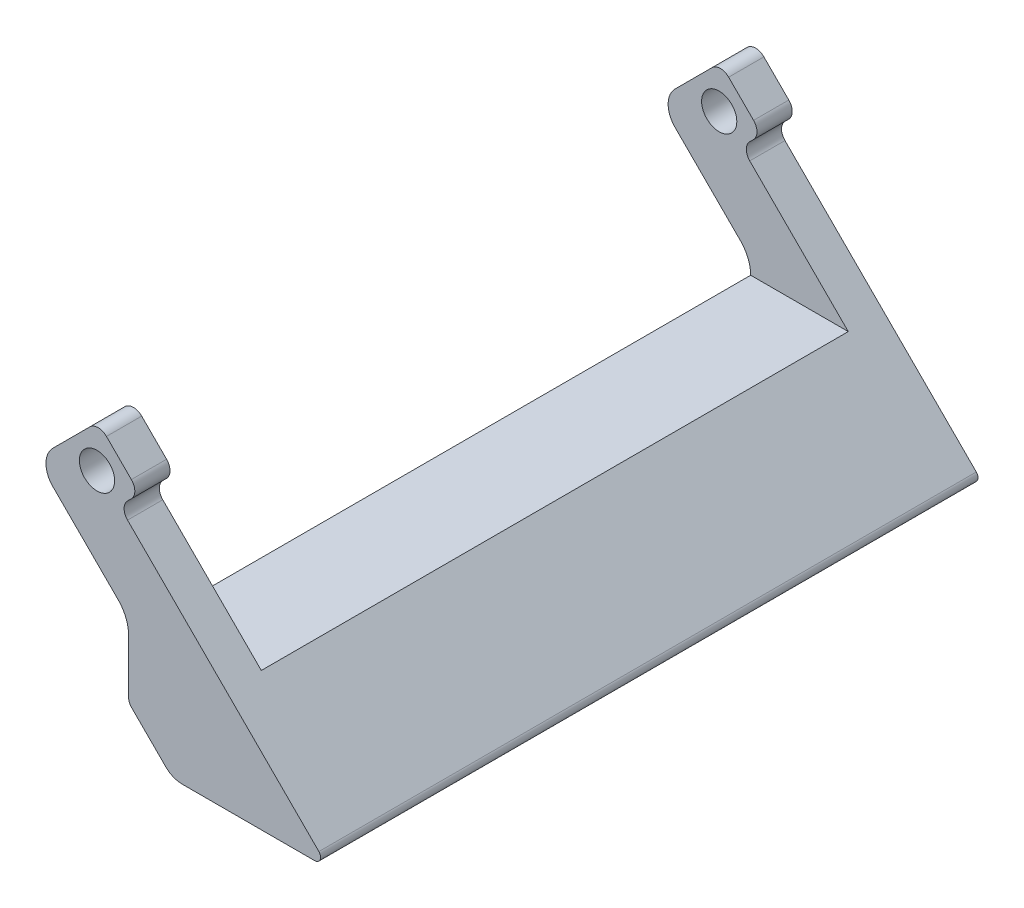
SolidWorks part; units mm, degrees
material "1060-H12"
ref_plane "Front Plane" through (0, 0, 0) normal (0, 0, 1) x (1, 0, 0)
ref_plane "Top Plane" through (0, 0, 0) normal (0, 1, 0) x (1, 0, 0)
ref_plane "Right Plane" through (0, 0, 0) normal (1, 0, 0) x (0, 0, -1)
sketch "Sketch1" plane through (0, 0, 0) normal (0, 0, 1) x (1, 0, 0)
  line L0 (30.0967, -21) -> (76.9648, -21)
  line L1 (3.6822, -19.5) -> (18.5462, -19.5)
  line L2 (-9.1152, 9.3685) -> (-1.6411, 1.8944)
  line L3 (2.6015, -0.934) -> (2.9274, -0.6081)
  line L4 (2.9274, 0.8061) -> (0.8061, 2.9274)
  line L5 (-0.6081, 2.9274) -> (-1.6411, 1.8944)
  line L6 (-1.6411, 1.8944) -> (-3.7625, -0.2269)
  line L7 (-3.7625, -3.0553) -> (1.8035, -8.6213)
  line L8 (2.6822, -10.7426) -> (2.6822, -18.5)
  line L9 (2.6015, -2.3482) -> (18.8997, -18.6464)
  circle A0 centre (0, 0) radius 1.5
  circle A1 centre (30.0967, 0.35) radius 21.35
  arc A2 (2.9274, -0.6081) -> (2.9274, 0.8061) centre (2.2203, 0.099) ccw
  arc A3 (0.8061, 2.9274) -> (-0.6081, 2.9274) centre (0.099, 2.2203) ccw
  arc A4 (2.6822, -18.5) -> (3.6822, -19.5) centre (3.6822, -18.5) ccw
  arc A5 (2.6015, -0.934) -> (2.6015, -2.3482) centre (3.3086, -1.6411) ccw
  arc A6 (-3.7625, -0.2269) -> (-3.7625, -3.0553) centre (-2.3482, -1.6411) ccw
  arc A7 (18.5462, -19.5) -> (18.8997, -18.6464) centre (18.5462, -19) ccw
  arc A8 (1.8035, -8.6213) -> (2.6822, -10.7426) centre (-0.3178, -10.7426) cw
  point P10 (15, -14.7467)
  point P23 (2.6822, -19.5)
  point P26 (1.8944, -1.6411)
  point P33 (2.6822, -9.5)
  dimension "D1" = 3
  dimension "D4" = 42.7
  dimension "D12" = 1
  dimension "D13" = 1
  dimension "D14" = 2
  dimension "D15" = 0.5
  dimension "D16" = 3
  dimension "D2" = 21
  dimension "D3" = 1.5
  dimension "D5" = 45
  dimension "D6" = 15
  dimension "D7" = 2.5
  dimension "D8" = 2.5
  dimension "D9" = 10
  dimension "D10" = 5
  dimension "D11" = 2.64
extrude "Boss-Extrude1" add sketch "Sketch1" along normal blind 3 contours L7 A8 L8 A4 L1 A7 L9 A5 L3 A2 L4 A3 L5 L6 A6 A0
sketch "Sketch2" plane through (0, 0, 3) normal (0, 0, 1) x (1, 0, 0)
  line L0 (2.6015, -2.3482) -> (18.8997, -18.6464) construction
  line L1 (3.6822, -19.5) -> (18.5462, -19.5) construction
  line L2 (2.6822, -10.7426) -> (2.6822, -18.5) construction
  line L3 (2.6015, -2.3482) -> (18.8997, -18.6464)
  line L4 (3.6822, -19.5) -> (18.5462, -19.5)
  line L5 (2.6822, -10.7426) -> (2.6822, -18.5)
  line L6 (2.6822, -10.7426) -> (10.9959, -10.7426)
  arc A0 (18.5462, -19.5) -> (18.8997, -18.6464) centre (18.5462, -19) ccw construction
  arc A1 (2.6822, -18.5) -> (3.6822, -19.5) centre (3.6822, -18.5) ccw construction
  arc A2 (18.5462, -19.5) -> (18.8997, -18.6464) centre (18.5462, -19) ccw
  arc A3 (2.6822, -18.5) -> (3.6822, -19.5) centre (3.6822, -18.5) ccw
  line M4 (2.6822, -10.7426) -> (2.6822, -18.5)
  arc M5 (2.6822, -18.5) -> (3.6822, -19.5) centre (3.6822, -18.5) ccw
  line M6 (3.6822, -19.5) -> (18.5462, -19.5)
  arc M7 (18.5462, -19.5) -> (18.8997, -18.6464) centre (18.5462, -19) ccw
  line M8 (18.8997, -18.6464) -> (2.6015, -2.3482)
extrude "Boss-Extrude2" add sketch "Sketch2" along normal blind 25 contours L6 M4 M5 M6 M7 M8
mirror "Mirror1" about plane through (0, 0, 28) normal (0, 0, 1) of "Boss-Extrude1", "Boss-Extrude2"
sketch "Sketch3" plane through (2.6822, 0, 0) normal (-1, 0, 0) x (0, 0, 1)
  line L0 (0, -15.7426) -> (56, -15.7426)
  line L1 (0, -10.7426) -> (0, -18.5) construction
  line L2 (56, -10.7426) -> (56, -18.5) construction
  line L3 (53, -10.7426) -> (3, -10.7426) construction
  dimension "D1" = 5
ref_plane "Plane1" through (-6.5302, -6.5302, 0) normal (-0.7071, -0.7071, 0) x (0, 0, 1)
sketch "Sketch6" plane through (-6.5302, -6.5302, 0) normal (-0.7071, -0.7071, 0) x (0, 0, 1)
  line L1 (56, -13.0283) -> (0, -13.0283)
  line L2 (56, -13.0283) -> (56, -22.1438)
  line L3 (56, -22.1438) -> (0, -22.1438)
  line L4 (0, -13.0283) -> (0, -22.1438)
extrude "Cut-Extrude1" cut sketch "Sketch6" along normal through all
fillet "Fillet1" radius 2 1 edges at (6.4396, -19.5, 28)
fillet "Fillet2" radius 1 1 edges at (2.6822, -15.7426, 28)
